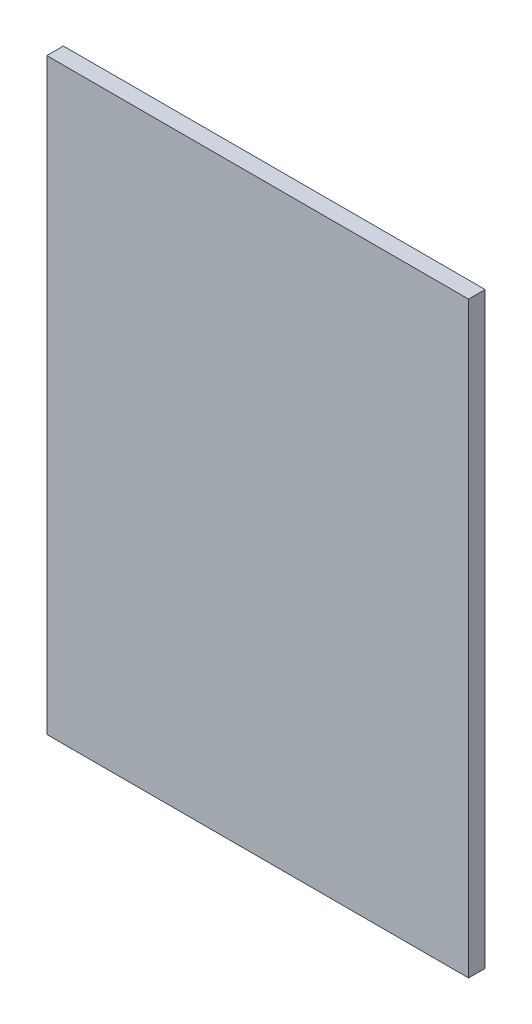
SolidWorks part; units mm, degrees
ref_plane "Front Plane" through (0, 0, 0) normal (0, 0, 1) x (1, 0, 0)
ref_plane "Top Plane" through (0, 0, 0) normal (0, 1, 0) x (1, 0, 0)
ref_plane "Right Plane" through (0, 0, 0) normal (1, 0, 0) x (0, 0, -1)
sketch "Sketch1" plane through (0, 0, 0) normal (0, 0, 1) x (1, 0, 0)
  line L1 (-40.3225, -56.1975) -> (40.3225, -56.1975)
  line L2 (-40.3225, -56.1975) -> (-40.3225, 56.1975)
  line L3 (-40.3225, 56.1975) -> (40.3225, 56.1975)
  line L4 (40.3225, -56.1975) -> (40.3225, 56.1975)
  line L5 (-40.3225, -56.1975) -> (40.3225, 56.1975) construction
  line L6 (-40.3225, 56.1975) -> (40.3225, -56.1975) construction
  point P0 (0, 0)
extrude "Boss-Extrude1" add sketch "Sketch1" along normal blind 3.175
